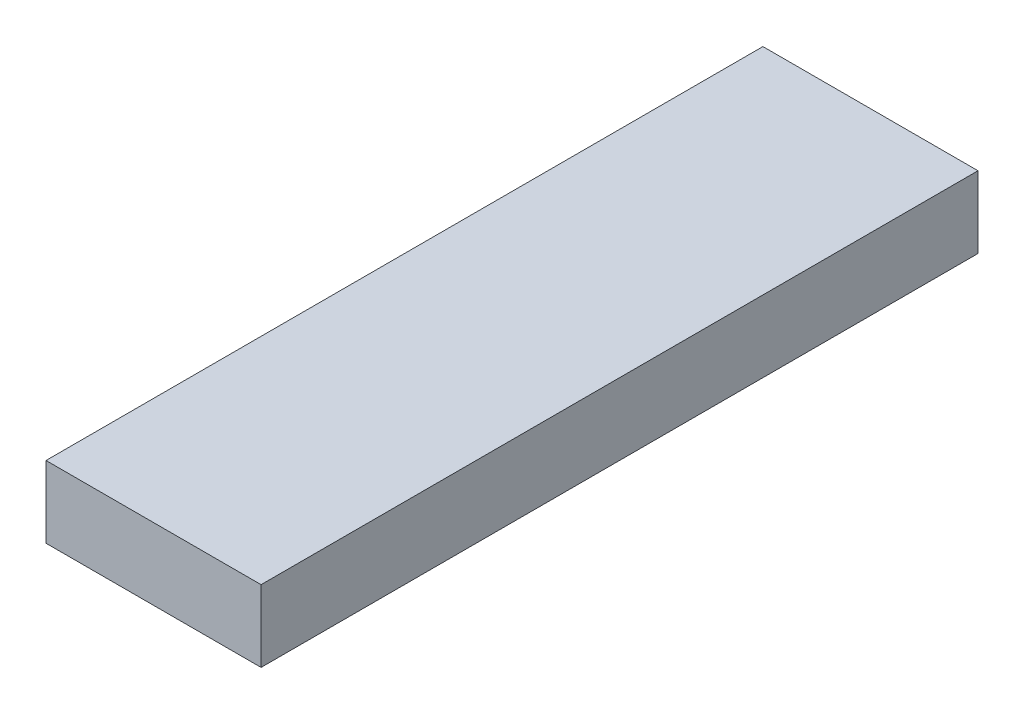
SolidWorks part; units mm, degrees
ref_plane "前视基准面" through (0, 0, 0) normal (0, 0, 1) x (1, 0, 0)
ref_plane "上视基准面" through (0, 0, 0) normal (0, 1, 0) x (1, 0, 0)
ref_plane "右视基准面" through (0, 0, 0) normal (1, 0, 0) x (0, 0, -1)
sketch "草图2" plane through (0, 0, 0) normal (0, 0, 1) x (1, 0, 0)
  line L1 (-90, -30) -> (90, -30)
  line L2 (-90, -30) -> (-90, 30)
  line L3 (-90, 30) -> (90, 30)
  line L4 (90, -30) -> (90, 30)
  line L5 (-90, -30) -> (90, 30) construction
  line L6 (-90, 30) -> (90, -30) construction
  point P0 (0, 0)
extrude "凸台-拉伸1" add sketch "草图2" along normal blind 600
